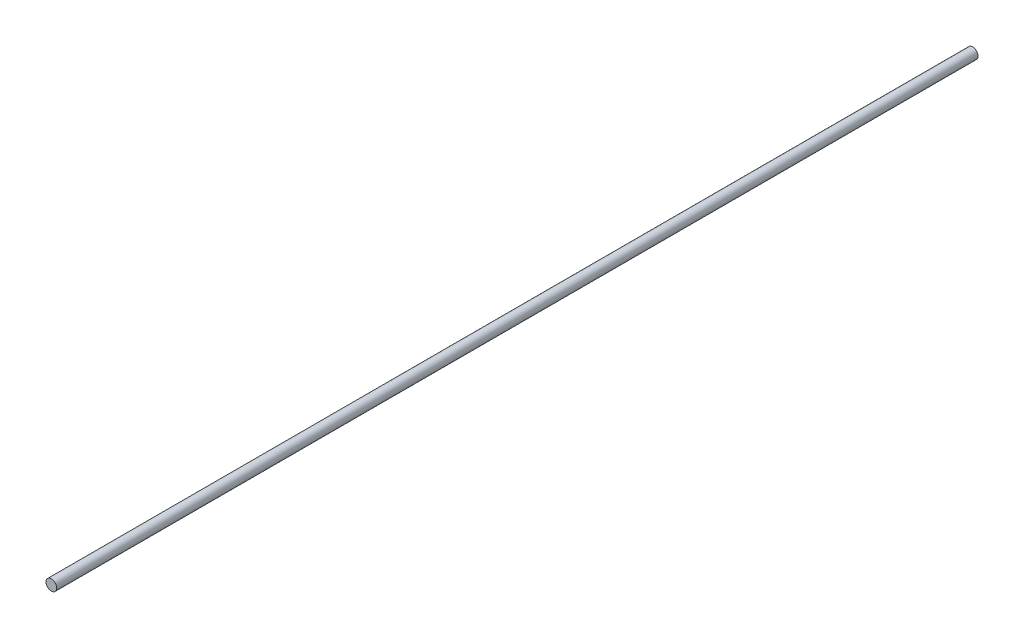
SolidWorks part; units mm, degrees
ref_plane "前视基准面" through (0, 0, 0) normal (0, 0, 1) x (1, 0, 0)
ref_plane "上视基准面" through (0, 0, 0) normal (0, 1, 0) x (1, 0, 0)
ref_plane "右视基准面" through (0, 0, 0) normal (1, 0, 0) x (0, 0, -1)
other "Configuration Table"
sketch "草图1" plane through (0, 0, 0) normal (0, 0, 1) x (1, 0, 0)
  circle A0 centre (0, -0.1964) radius 2.5
  dimension "D1" = 5
extrude "凸台-拉伸1" add sketch "草图1" along normal blind 433.07
